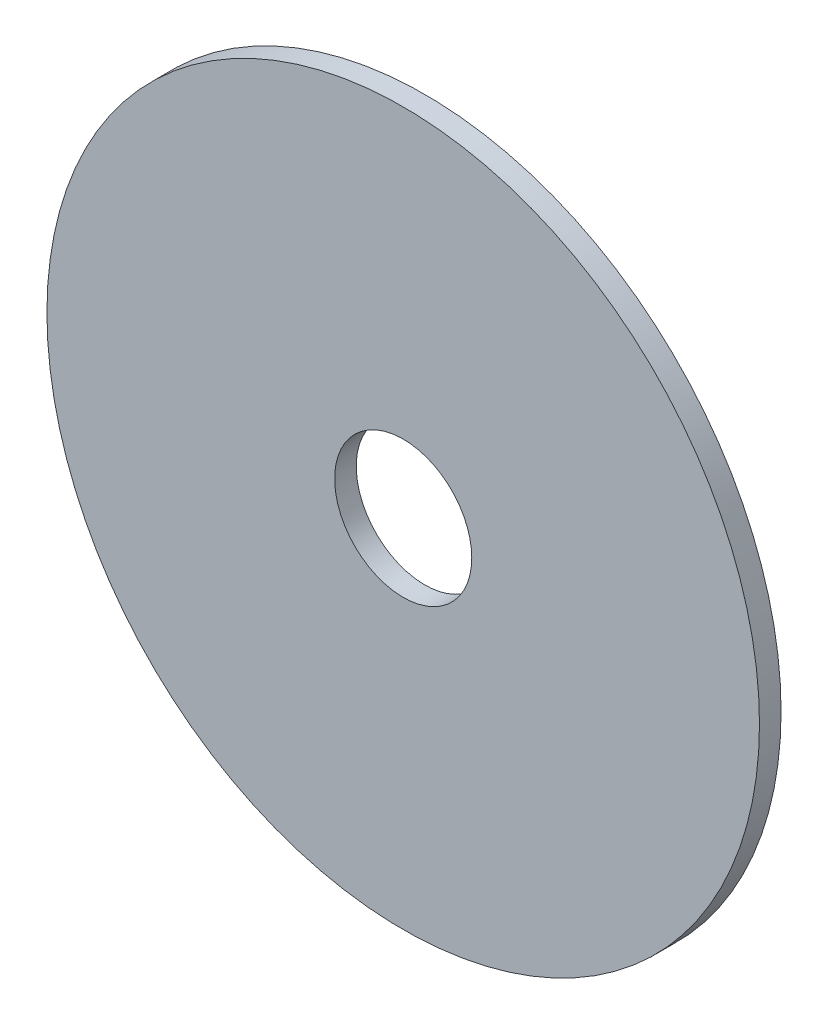
SolidWorks part; units mm, degrees
material "Thornel Mat VMA"
ref_plane "Front Plane" through (0, 0, 0) normal (0, 0, 1) x (1, 0, 0)
ref_plane "Top Plane" through (0, 0, 0) normal (0, 1, 0) x (1, 0, 0)
ref_plane "Right Plane" through (0, 0, 0) normal (1, 0, 0) x (0, 0, -1)
sketch "Sketch1" plane through (0, 0, 0) normal (0, 0, 1) x (1, 0, 0)
  circle A0 centre (0, 0) radius 33
  circle A1 centre (0, 0) radius 6.35 construction
  circle A2 centre (0, 0) radius 6.35
  dimension "D1" = 66
extrude "Boss-Extrude1" add sketch "Sketch1" along normal blind 2
